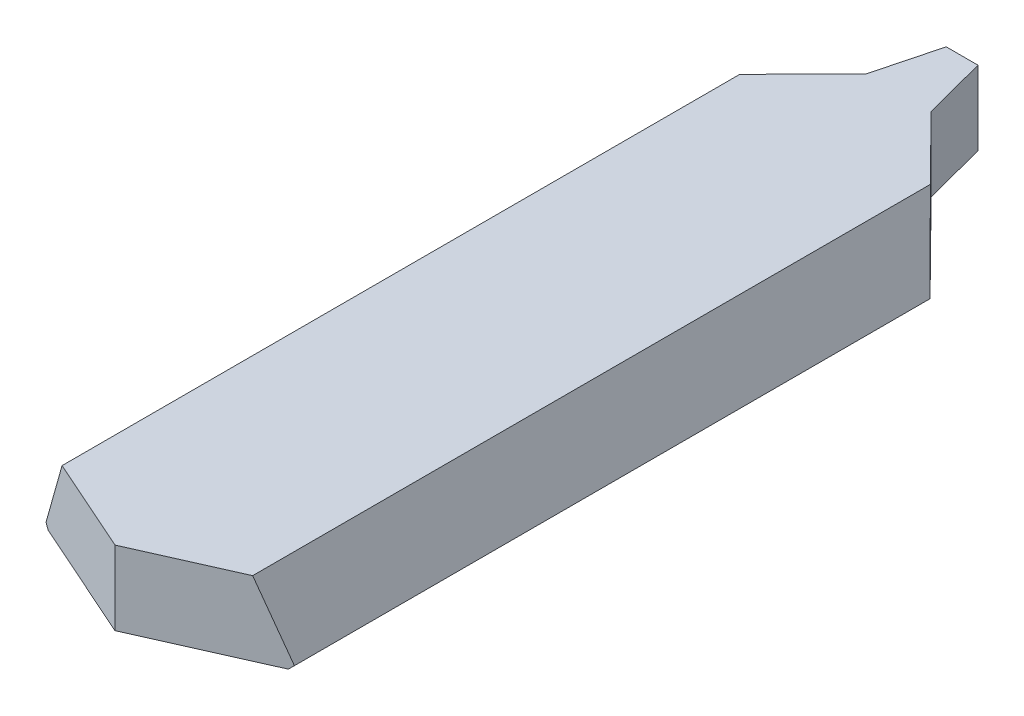
SolidWorks part; units mm, degrees
ref_plane "Front Plane" through (0, 0, 0) normal (0, 0, 1) x (1, 0, 0)
ref_plane "Top Plane" through (0, 0, 0) normal (0, 1, 0) x (1, 0, 0)
ref_plane "Right Plane" through (0, 0, 0) normal (1, 0, 0) x (0, 0, -1)
sketch "Sketch1" plane through (0, 0, 0) normal (0, 1, 0) x (1, 0, 0)
  line L0 (0, 22) -> (0, 0) construction
  line L1 (-9, 22) -> (9, 22) construction
  line L2 (-9, 22) -> (-9, -58) construction
  line L3 (-9, -58) -> (9, -58) construction
  line L4 (9, 22) -> (9, -58) construction
  line L5 (0, 0) -> (9, 0) construction
  line L6 (-9, -54) -> (-9, 10) construction
  line L7 (0, 0) -> (-9, 0) construction
  line L8 (0, 0) -> (0, -58) construction
  line L9 (-9, -54) -> (0, -58)
  line L10 (0, -58) -> (9, -54)
  line L11 (9, -54) -> (9, 10)
  line L13 (9, 10) -> (-9, 10) construction
  line L14 (9, 10) -> (0, 10) construction
  line L16 (-9, 10) -> (-9, -54)
  line L20 (1.5, 22) -> (-1.5, 22) construction
  line L21 (-9, 10) -> (-3.07, 16)
  line L22 (-3.07, 16) -> (-1.5, 22)
  line L23 (-1.5, 22) -> (1.5, 22)
  line L24 (1.5, 22) -> (3.07, 16)
  line L25 (3.07, 16) -> (9, 10)
sketch "Sketch2" plane through (0, 0, 0) normal (0, 0, 1) x (1, 0, 0)
  line L0 (9, 0) -> (11.7304, -6.6079)
  line L1 (11.7304, -6.6079) -> (11.3369, -7)
  line L2 (11.3369, -7) -> (-11.3369, -7)
  line L3 (-11.3369, -7) -> (-11.7304, -6.6079)
  line L5 (-11.7304, -6.6079) -> (-9, 0)
  line L6 (-9, 0) -> (9, 0)
extrude "Boss-Extrude1" add sketch "Sketch2" along normal up to vertex (58 mm away) from vertex at -22 starting at point (-9, 0, -22)
sketch "Sketch3" plane through (0, 0, 0) normal (0, 1, 0) x (1, 0, 0)
  line L0 (-11.7304, 7.2374) -> (-3.07, 16)
  line L1 (-3.07, 16) -> (-1.5, 22)
  line L2 (11.7304, 7.2374) -> (11.7304, -52.7865)
  line L3 (11.7304, -52.7865) -> (0, -58)
  line L4 (0, -58) -> (-11.7304, -52.7865)
  line L5 (-11.7304, -52.7865) -> (-11.7304, 7.2374)
  line L6 (-1.5, 22) -> (1.5, 22)
  line L7 (1.5, 22) -> (3.07, 16)
  line L10 (0, -58) -> (9, -54) construction
  line L11 (-9, -54) -> (0, -58) construction
  line L12 (0, -58) -> (0, 32.6351) construction
  line L13 (3.07, 16) -> (11.7304, 7.2374)
  line L14 (3.07, 16) -> (9, 10) construction
  line L15 (-9, 10) -> (-3.07, 16) construction
extrude "Cut-Extrude1" cut sketch "Sketch3" against normal through all flip side to cut
